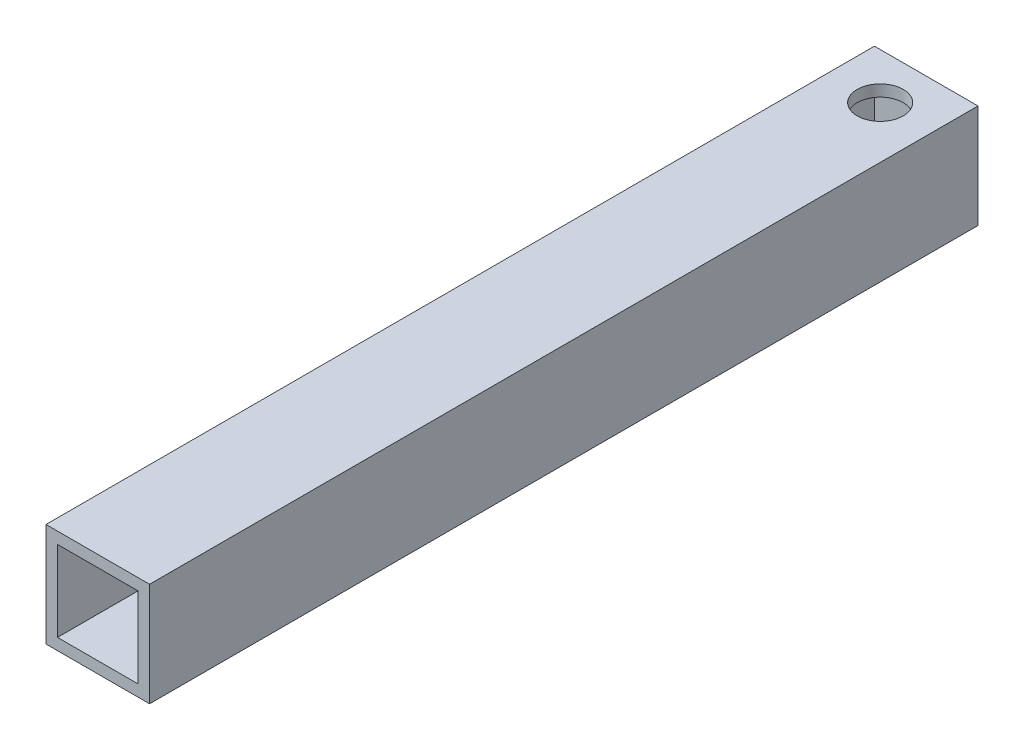
SolidWorks part; units mm, degrees
ref_plane "Front Plane" through (0, 0, 0) normal (0, 0, 1) x (1, 0, 0)
ref_plane "Top Plane" through (0, 0, 0) normal (0, 1, 0) x (1, 0, 0)
ref_plane "Right Plane" through (0, 0, 0) normal (1, 0, 0) x (0, 0, -1)
sketch "Sketch1" plane through (0, 0, 0) normal (0, 0, 1) x (1, 0, 0)
  line L0 (-28.575, -28.575) -> (28.575, -28.575)
  line L1 (-22.225, -22.225) -> (22.225, -22.225)
  line L2 (-22.225, -22.225) -> (-22.225, 22.225)
  line L3 (-22.225, 22.225) -> (22.225, 22.225)
  line L4 (22.225, -22.225) -> (22.225, 22.225)
  line L5 (-22.225, -22.225) -> (22.225, 22.225) construction
  line L6 (-22.225, 22.225) -> (22.225, -22.225) construction
  line L7 (28.575, -28.575) -> (28.575, 28.575)
  line L8 (-28.575, 28.575) -> (28.575, 28.575)
  line L9 (-28.575, -28.575) -> (-28.575, 28.575)
  point P0 (0, 0)
  point P6 (0, 0)
  dimension "D1" = 44.45
  dimension "D2" = 44.45
  dimension "D3" = 6.35
extrude "Boss-Extrude1" add sketch "Sketch1" along normal blind 457.2
sketch "Sketch2" plane through (0, -22.225, 0) normal (0, 1, 0) x (1, 0, 0)
  line L0 (22.225, -457.2) -> (22.225, 0) construction
  line L1 (-22.225, 0) -> (22.225, 0)
  line L2 (-22.225, 0) -> (-22.225, -6.35)
  line L3 (-22.225, -6.35) -> (22.225, -6.35)
  line L4 (22.225, 0) -> (22.225, -6.35)
  dimension "D1" = 6.35
extrude "Boss-Extrude2" add sketch "Sketch2" along normal up to surface (44.45 mm away) up to face at (0, 22.225, 228.6)
sketch "Sketch3" plane through (0, 28.575, 0) normal (0, 1, 0) x (0, 0, -1)
  line L2 (-457.2, -28.575) -> (0, -28.575) construction
  line L3 (0, 28.575) -> (0, -28.575) construction
  circle A0 centre (-25.4, 0) radius 12.7
  point P2 (-29.4001, 0)
  dimension "D1" = 25.4
  dimension "D2" = 28.575
  dimension "D3" = 25.4
extrude "Cut-Extrude1" cut sketch "Sketch3" along direction (0, -1, 0) on the side against the normal up to surface (6.35 mm away) contours A0
